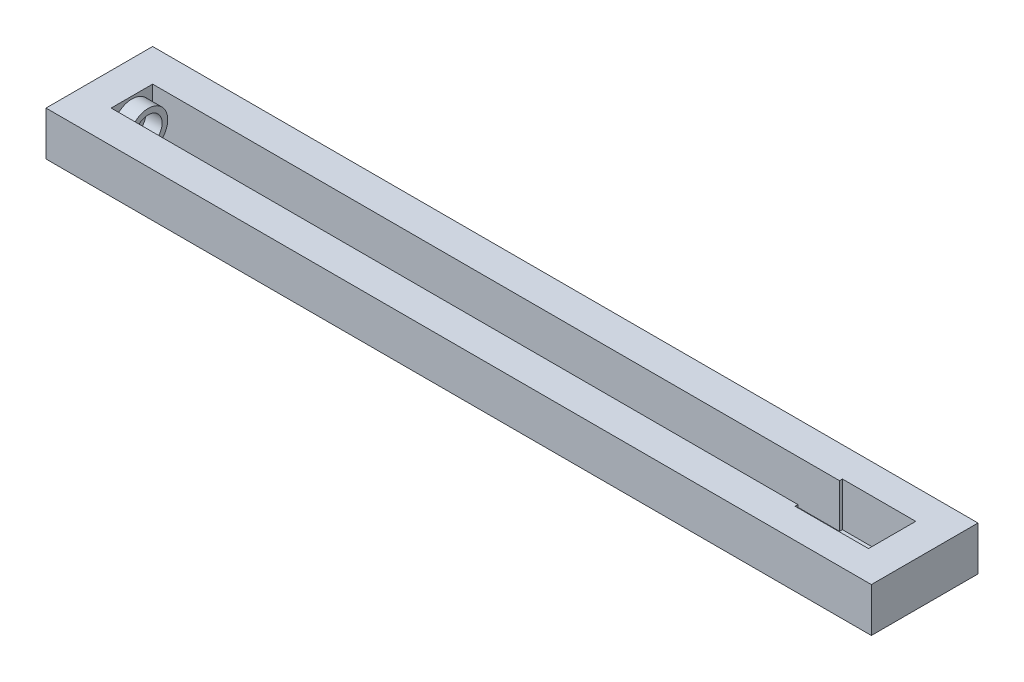
SolidWorks part; units mm, degrees
material "201 Annealed Stainless Steel (SS)"
ref_plane "Front Plane" through (0, 0, 0) normal (0, 0, 1) x (1, 0, 0)
ref_plane "Top Plane" through (0, 0, 0) normal (0, 1, 0) x (1, 0, 0)
ref_plane "Right Plane" through (0, 0, 0) normal (1, 0, 0) x (0, 0, -1)
sketch "Sketch1" plane through (0, 0, 0) normal (0, 1, 0) x (1, 0, 0)
  line L0 (-380, 49.1) -> (380, 49.1)
  line L1 (-350, 19.1) -> (350, 19.1)
  line L2 (-350, 19.1) -> (-350, -19.1)
  line L3 (-350, -19.1) -> (350, -19.1)
  line L4 (350, 19.1) -> (350, -19.1)
  line L5 (-350, 19.1) -> (350, -19.1) construction
  line L6 (-350, -19.1) -> (350, 19.1) construction
  line L7 (380, 49.1) -> (380, -49.1)
  line L8 (-380, -49.1) -> (380, -49.1)
  line L9 (-380, 49.1) -> (-380, -49.1)
  point P0 (0, 0)
  dimension "D1" = 38.2
  dimension "D2" = 700
  dimension "D3" = 30
extrude "Boss-Extrude3" add sketch "Sketch1" along normal blind 40.64
sketch "Sketch2" plane through (0, 0, 0) normal (0, -1, 0) x (1, 0, 0)
  line L1 (-350, 19.1) -> (350, 19.1)
  line L2 (-350, 19.1) -> (-350, -19.1)
  line L3 (-350, -19.1) -> (350, -19.1)
  line L4 (350, 19.1) -> (350, -19.1)
  line L5 (-350, 19.1) -> (350, -19.1) construction
  line L6 (-350, -19.1) -> (350, 19.1) construction
  point P0 (0, 0)
extrude "Boss-Extrude4" add sketch "Sketch2" against normal blind 0.254
sketch "Sketch3" plane through (0, 40.64, 0) normal (0, 1, 0) x (1, 0, 0)
  line L0 (380, 0) -> (143.674, 0) construction
  line L1 (350, 21.75) -> (282.5, 21.75)
  line L2 (350, 21.75) -> (350, -21.75)
  line L3 (350, -21.75) -> (282.5, -21.75)
  line L4 (282.5, 21.75) -> (282.5, -21.75)
  line L5 (380, -49.1) -> (380, 49.1) construction
  line L6 (350, -19.1) -> (350, 19.1) construction
  point P9 (350, 0)
  dimension "D1" = 43.5
  dimension "D2" = 67.5
  dimension "D3" = 0
extrude "Cut-Extrude1" cut sketch "Sketch3" against normal up to surface (40.386 mm away) up to face at (0, 0.254, 0)
sketch "Sketch6" plane through (-350, 0, 0) normal (1, 0, 0) x (0, 0, -1)
  line L0 (0, 43.1998) -> (0, -9.7567) construction
  line L1 (49.1, 20.32) -> (-49.1, 20.32) construction
  line L2 (49.1, 40.64) -> (49.1, 0) construction
  line L3 (-49.1, 40.64) -> (-49.1, 0) construction
  circle A0 centre (0, 20.32) radius 12.8397
  circle A1 centre (0, 20.32) radius 18
  dimension "D1" = 25.6794
  dimension "D2" = 36
extrude "Boss-Extrude5" add sketch "Sketch6" along normal blind 15
sketch "Sketch7" plane through (0, 0, 0) normal (0, -1, 0) x (1, 0, 0)
  line L0 (-380, 0) -> (380, 0) construction
  line L1 (-380, -49.1) -> (-380, 49.1) construction
  line L2 (380, 49.1) -> (380, -49.1) construction
  line L3 (0, 49.1) -> (0, -49.1) construction
  line L4 (-380, 49.1) -> (380, 49.1) construction
  line L5 (380, -49.1) -> (-380, -49.1) construction
  line L7 (-19.05, -22.185) -> (19.05, -22.185)
  line L8 (-19.05, -22.185) -> (-19.05, 22.185)
  line L9 (-19.05, 22.185) -> (19.05, 22.185)
  line L10 (19.05, -22.185) -> (19.05, 22.185)
  line L11 (-19.05, -22.185) -> (19.05, 22.185) construction
  line L12 (-19.05, 22.185) -> (19.05, -22.185) construction
  point P12 (0, 0)
  dimension "D1" = 44.37
  dimension "D2" = 38.1
extrude "Boss-Extrude6" add sketch "Sketch7" along normal blind 20
